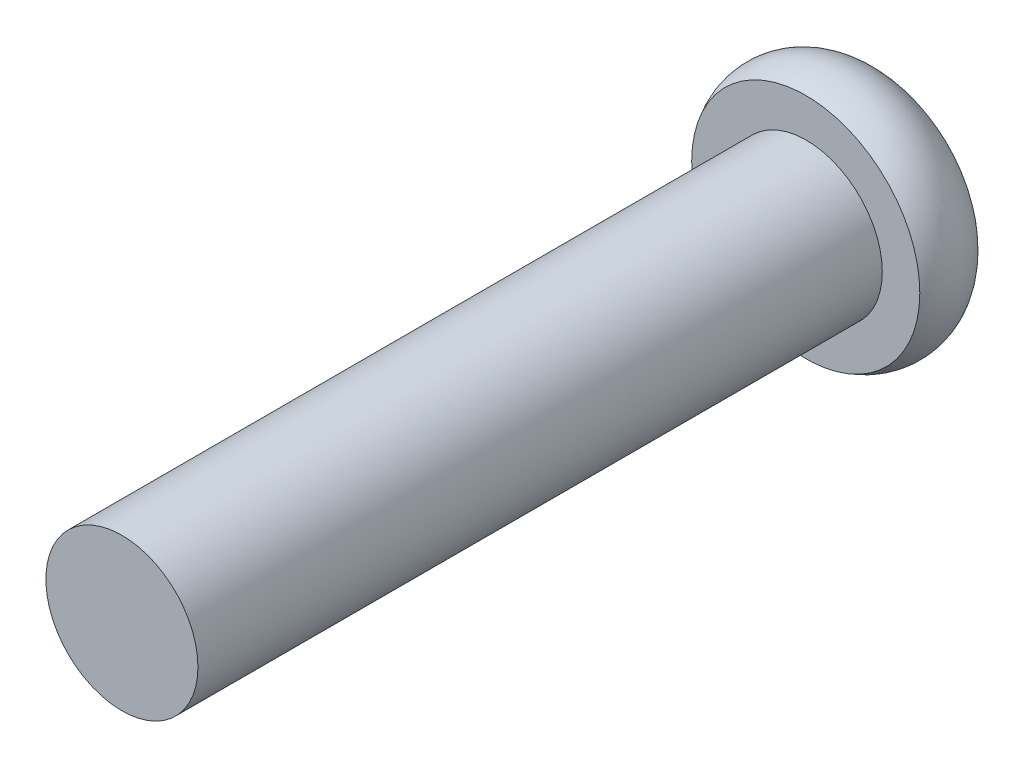
SolidWorks part; units mm, degrees
ref_plane "Front Plane" through (0, 0, 0) normal (0, 0, 1) x (1, 0, 0)
ref_plane "Top Plane" through (0, 0, 0) normal (0, 1, 0) x (1, 0, 0)
ref_plane "Right Plane" through (0, 0, 0) normal (1, 0, 0) x (0, 0, -1)
sketch "Sketch1" plane through (0, 0, 0) normal (0, 1, 0) x (1, 0, 0)
  line L0 (0, 0.6593) -> (0, 4.5218) construction
  line L3 (0, 0) -> (0, 2)
  line L4 (0, 0) -> (3, 0)
  line L5 (0, 2) -> (2.2983, 2)
  arc A0 (2.5735, 1.9174) -> (3, 0) centre (1.7961, 0.7384) cw
  arc A1 (2.5735, 1.9174) -> (2.2983, 2) centre (2.2983, 1.5) ccw
  dimension "D2" = 0.5
revolve "Revolve2" add sketch "Sketch1" angle 360 about L0
sketch "Sketch2" plane through (0, 0, -2) normal (0, 0, -1) x (-1, 0, 0)
  line L0 (0, 0) -> (2.5296, 0) construction
  line L1 (0, 0) -> (0, 1.7464) construction
  line L2 (0.5, -0.5) -> (2, -0.5)
  line L3 (-0.5, 2) -> (0.5, 2)
  line L4 (-0.5, 2) -> (-0.5, 0.5)
  line L5 (-0.5, -2) -> (0.5, -2)
  line L6 (0.5, 2) -> (0.5, 0.5)
  line L7 (0.5, 0.5) -> (2, 0.5)
  line L8 (0.5, -0.5) -> (0.5, -2)
  line L9 (-2, 0.5) -> (-0.5, 0.5)
  line L10 (-2, 0.5) -> (-2, -0.5)
  line L11 (-2, -0.5) -> (-0.5, -0.5)
  line L12 (2, 0.5) -> (2, -0.5)
  line L15 (-0.5, -0.5) -> (-0.5, -2)
  point P4 (0, 0)
  point P12 (0, 0)
  dimension "D1" = 0.5
  dimension "D2" = 2
  dimension "D3" = 2
  dimension "D4" = 2
  dimension "D5" = 0.5
  dimension "D6" = 0.5
  dimension "D7" = 0.5
  dimension "D8" = 0.5
extrude "Cut-Extrude1" cut sketch "Sketch2" against normal blind 2 draft 12
sketch "Sketch3" plane through (0, 0, 0) normal (0, 0, 1) x (1, 0, 0)
  circle A0 centre (0.0136, -0.0136) radius 2
extrude "Boss-Extrude1" add sketch "Sketch3" along normal blind 18
cosmetic thread "Cosmetic Thread2" parameters "D2"=2.439
